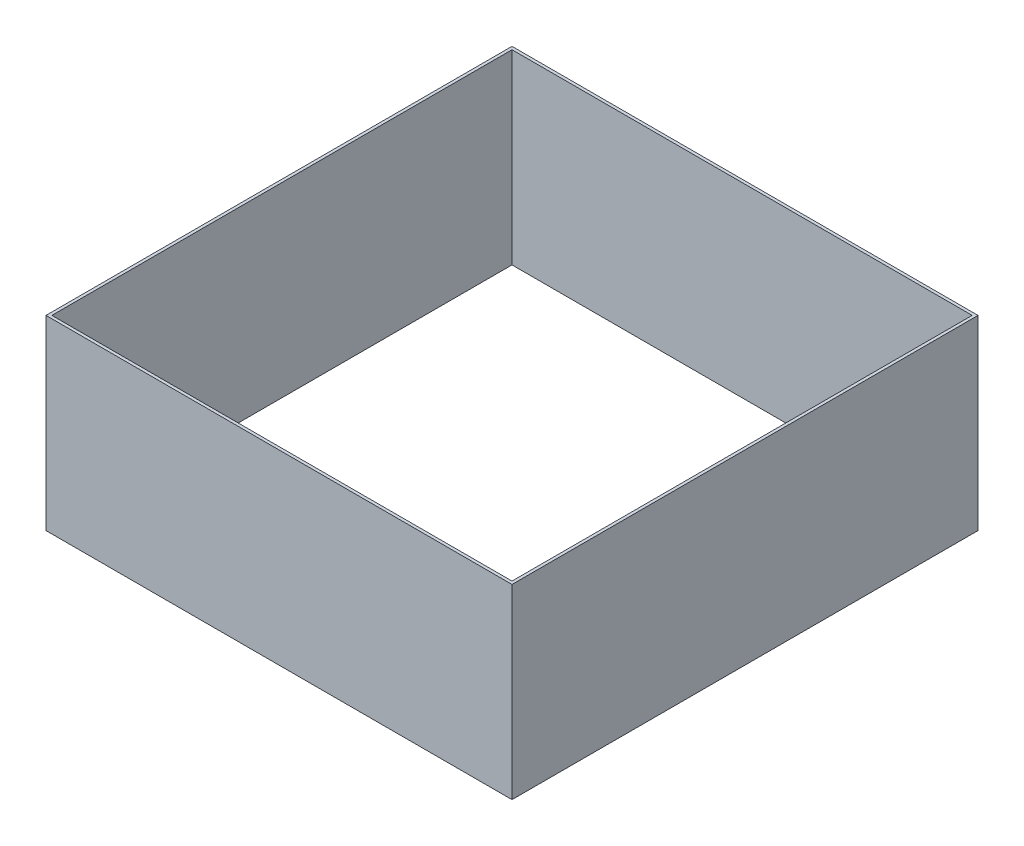
SolidWorks part; units mm, degrees
ref_plane "Front Plane" through (0, 0, 0) normal (0, 0, 1) x (1, 0, 0)
ref_plane "Top Plane" through (0, 0, 0) normal (0, 1, 0) x (1, 0, 0)
ref_plane "Right Plane" through (0, 0, 0) normal (1, 0, 0) x (0, 0, -1)
sketch "Sketch2" plane through (0, 0, 0) normal (0, 1, 0) x (1, 0, 0)
  line L0 (0, 20) -> (40, 20) construction
  line L1 (0, 0) -> (40, 0)
  line L2 (0, 0) -> (0, 40)
  line L3 (0, 40) -> (40, 40)
  line L4 (40, 0) -> (40, 40)
  line L5 (20, 40) -> (20, 0) construction
  line L7 (0.25, 39.75) -> (39.75, 39.75)
  line L8 (0.25, 39.75) -> (0.25, 0.25)
  line L9 (0.25, 0.25) -> (39.75, 0.25)
  line L10 (39.75, 39.75) -> (39.75, 0.25)
  line L11 (0.25, 39.75) -> (39.75, 0.25) construction
  line L12 (0.25, 0.25) -> (39.75, 39.75) construction
  point P9 (20, 20)
  dimension "D1" = 40
  dimension "D2" = 40
  dimension "D3" = 0.25
  dimension "D4" = 0.25
extrude "Boss-Extrude4" add sketch "Sketch2" along normal blind 16
sketch "Sketch4" plane through (0, 0, 0) normal (0, -1, 0) x (1, 0, 0)
  line L1 (0, 0) -> (40, 0)
  line L2 (0, 0) -> (0, -40)
  line L3 (0, -40) -> (40, -40)
  line L4 (40, 0) -> (40, -40)
